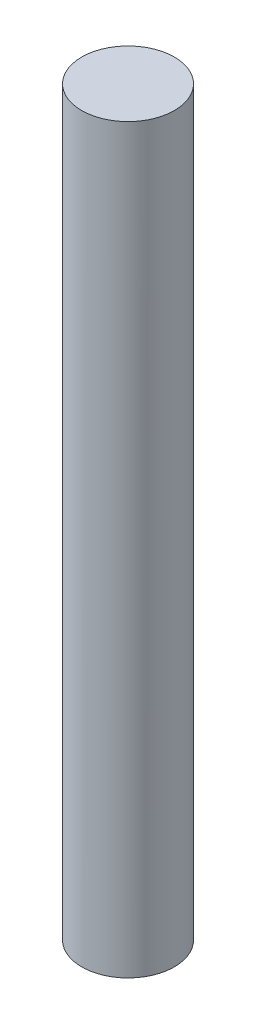
SolidWorks part; units mm, degrees
ref_plane "Ön Düzlem" through (0, 0, 0) normal (0, 0, 1) x (1, 0, 0)
ref_plane "Üst Düzlem" through (0, 0, 0) normal (0, 1, 0) x (1, 0, 0)
ref_plane "Sağ Düzlem" through (0, 0, 0) normal (1, 0, 0) x (0, 0, -1)
sketch "Çizim1" plane through (0, 0, 0) normal (0, 1, 0) x (1, 0, 0)
  circle A0 centre (0, 0) radius 7.5
  dimension "D1" = 15
extrude "Yükseklik-Ekstrüzyon1" add sketch "Çizim1" along normal blind 40
sketch "Çizim2" plane through (0, 0, 0) normal (0, -1, 0) x (1, 0, 0)
  circle A0 centre (0, 0) radius 7.5
extrude "Yükseklik-Ekstrüzyon2" add sketch "Çizim2" along normal blind 80
